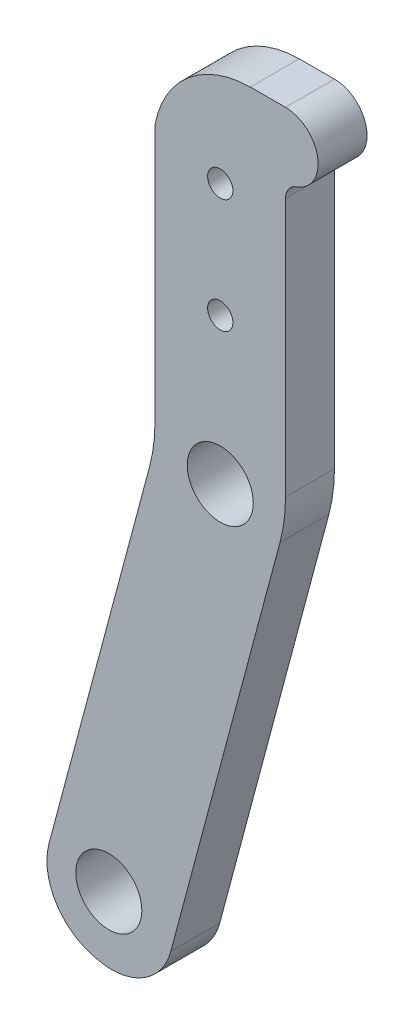
SolidWorks part; units mm, degrees
ref_plane "Płaszczyzna przednia" through (0, 0, 0) normal (0, 0, 1) x (1, 0, 0)
ref_plane "Płaszczyzna górna" through (0, 0, 0) normal (0, 1, 0) x (1, 0, 0)
ref_plane "Płaszczyzna prawa" through (0, 0, 0) normal (1, 0, 0) x (0, 0, -1)
sketch "Szkic1" plane through (0, 0, 0) normal (0, 0, 1) x (1, 0, 0)
  line L0 (183.4349, 83.6172) -> (183.4349, 42.2423)
  line L1 (183.4349, 83.6172) -> (167.4349, 83.6172)
  line L3 (167.4349, 83.6172) -> (167.4349, 42.2423)
  line L4 (182.7574, 37.081) -> (167.4349, -20.2828)
  line L5 (166.7574, 37.081) -> (152.5004, -16.2936)
  line L6 (167.4349, -20.2828) -> (152.5004, -16.2936)
  arc A0 (166.7574, 37.081) -> (167.4349, 42.2423) centre (147.4349, 42.2423) ccw
  arc A1 (183.4349, 42.2423) -> (182.7574, 37.081) centre (163.4349, 42.2423) cw
  point P10 (183.4349, 39.6172)
  dimension "D1" = 0
  dimension "D5" = 20
  dimension "D2" = 16
  dimension "D3" = 62
  dimension "D4" = 16
extrude "Dodanie-wyciągnięcie1" add sketch "Szkic1" along normal blind 6
sketch "Szkic2" plane through (0, 0, 6) normal (0, 0, 1) x (1, 0, 0)
  line L0 (183.4349, 42.2423) -> (183.4349, 83.6172) construction
  line L1 (183.4349, 83.6172) -> (167.4349, 83.6172) construction
  line L5 (183.4349, 42.2423) -> (183.4349, 83.6172) construction
  circle A0 centre (175.4349, 39.6172) radius 4.05
  circle A1 centre (175.4349, -14.3828) radius 4.05
  dimension "D1" = 8.1
  dimension "D2" = 8.1
  dimension "D3" = 8
  dimension "D4" = 8
  dimension "D5" = 44
  dimension "D6" = 54
extrude "Wytnij-wyciągnięcie1" cut sketch "Szkic2" against normal blind 6
sketch "Szkic4" plane through (0, 0, 6) normal (0, 0, 1) x (1, 0, 0)
  line L0 (167.4349, -20.2828) -> (182.7574, 37.081) construction
  line L1 (152.5004, -16.2936) -> (167.4349, -20.2828) construction
  circle A0 centre (161.7704, -10.4892) radius 4.05
  dimension "D1" = 8.1
  dimension "D2" = 8
  dimension "D3" = 8
extrude "Wytnij-wyciągnięcie4" cut sketch "Szkic4" against normal blind 6
sketch "Szkic5" plane through (0, 0, 6) normal (0, 0, 1) x (1, 0, 0)
  line L3 (167.4349, 73.7779) -> (167.4349, 83.6172)
  line L4 (167.4349, 83.6172) -> (179.1268, 83.6172)
  arc A0 (179.1268, 83.6172) -> (167.4349, 73.7779) centre (179.2388, 71.6177) ccw
  point P9 (167.4349, 83.6172)
  dimension "D1" = 12
extrude "Wytnij-wyciągnięcie5" cut sketch "Szkic5" against normal blind 6
sketch "Szkic6" plane through (0, 0, 6) normal (0, 0, 1) x (1, 0, 0)
  line L0 (183.4349, 42.2423) -> (183.4349, 83.6172) construction
  line L1 (183.4349, 83.6172) -> (179.1268, 83.6172) construction
  circle A0 centre (183.4349, 79.6172) radius 4
  dimension "D1" = 4
extrude "Dodanie-wyciągnięcie2" add sketch "Szkic6" against normal blind 6
sketch "Szkic7" plane through (0, 0, 6) normal (0, 0, 1) x (1, 0, 0)
  circle A0 centre (175.4349, 57.5308) radius 1.55 construction
  circle A1 centre (175.4349, 71.5308) radius 1.55 construction
  circle A2 centre (175.4349, 57.5308) radius 1.55
  circle A3 centre (175.4349, 71.5308) radius 1.55
extrude "Wytnij-wyciągnięcie6" cut sketch "Szkic7" against normal blind 10
sketch "Szkic8" plane through (0, 0, 6) normal (0, 0, 1) x (1, 0, 0)
  line L0 (184.7682, 75.8459) -> (183.0191, 76.0386)
  line L1 (183.0191, 76.0386) -> (183.4349, 73.9603)
  arc A0 (183.4349, 73.9603) -> (184.7682, 75.8459) centre (185.4349, 73.9603) cw
  dimension "D2" = 2
extrude "Dodanie-wyciągnięcie3" add sketch "Szkic8" against normal blind 6
sketch "Szkic10" plane through (0, 0, 6) normal (0, 0, 1) x (1, 0, 0)
  line L0 (169.3704, -13.0368) -> (167.4349, -20.2828)
  line L1 (167.4349, -20.2828) -> (160.1889, -18.3473)
  line L2 (154.4359, -9.0476) -> (152.5004, -16.2936)
  line L3 (152.5004, -16.2936) -> (159.7464, -18.2291)
  arc A0 (154.4359, -9.0476) -> (159.7464, -18.2291) centre (161.6819, -10.9831) ccw
  arc A1 (160.1889, -18.3473) -> (169.3704, -13.0368) centre (162.1244, -11.1013) ccw
  dimension "D2" = 7.5
extrude "Wytnij-wyciągnięcie7" cut sketch "Szkic10" against normal blind 6
